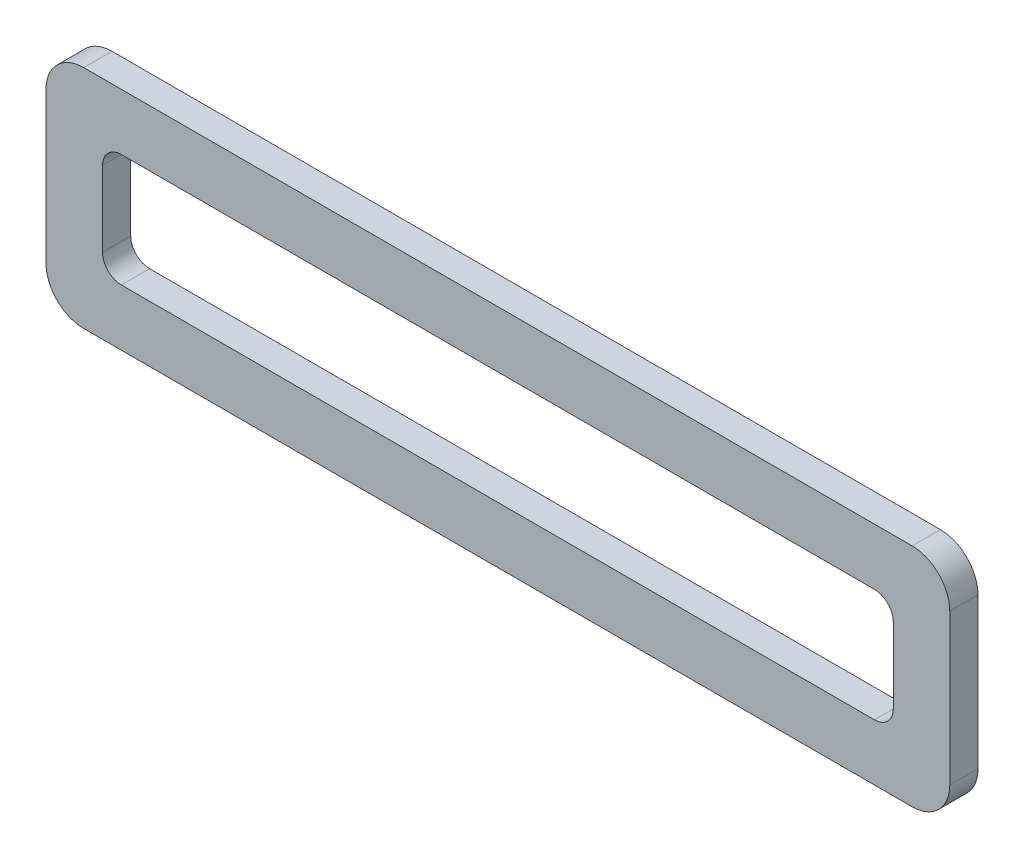
SolidWorks part; units mm, degrees
material "Rubber"
ref_plane "Front" through (0, 0, 0) normal (0, 0, 1) x (1, 0, 0)
ref_plane "Top" through (0, 0, 0) normal (0, 1, 0) x (1, 0, 0)
ref_plane "Right" through (0, 0, 0) normal (1, 0, 0) x (0, 0, -1)
sketch "Sketch1" plane through (0, 0, 0) normal (0, 0, 1) x (1, 0, 0)
  line L0 (0, 19.05) -> (0, 38.1) construction
  line L1 (-152.4, 38.1) -> (152.4, 38.1)
  line L2 (-152.4, 38.1) -> (-152.4, -38.1)
  line L3 (-152.4, -38.1) -> (152.4, -38.1)
  line L4 (152.4, 38.1) -> (152.4, -38.1)
  line L5 (-152.4, 38.1) -> (152.4, -38.1) construction
  line L6 (-152.4, -38.1) -> (152.4, 38.1) construction
  line L7 (-133.35, 19.05) -> (133.35, 19.05)
  line L8 (-133.35, 19.05) -> (-133.35, -19.05)
  line L9 (-133.35, -19.05) -> (133.35, -19.05)
  line L10 (133.35, 19.05) -> (133.35, -19.05)
  line L11 (-133.35, 19.05) -> (133.35, -19.05) construction
  line L12 (-133.35, -19.05) -> (133.35, 19.05) construction
  line L13 (-133.35, 0) -> (-152.4, 0) construction
  point P0 (0, 0)
  point P6 (0, 0)
  dimension "D1" = 19.05
  dimension "D2" = 304.8
  dimension "D3" = 76.2
extrude "Boss-Extrude1" add sketch "Sketch1" along normal blind 9.525
fillet "Fillet1" radius 12.7 4 edges at (-152.4, -38.1, 4.7625) (152.4, -38.1, 4.7625) (152.4, 38.1, 4.7625) (-152.4, 38.1, 4.7625)
fillet "Fillet2" radius 6.35 4 edges at (133.35, 19.05, 4.7625) (133.35, -19.05, 4.7625) (-133.35, -19.05, 4.7625) (-133.35, 19.05, 4.7625)
